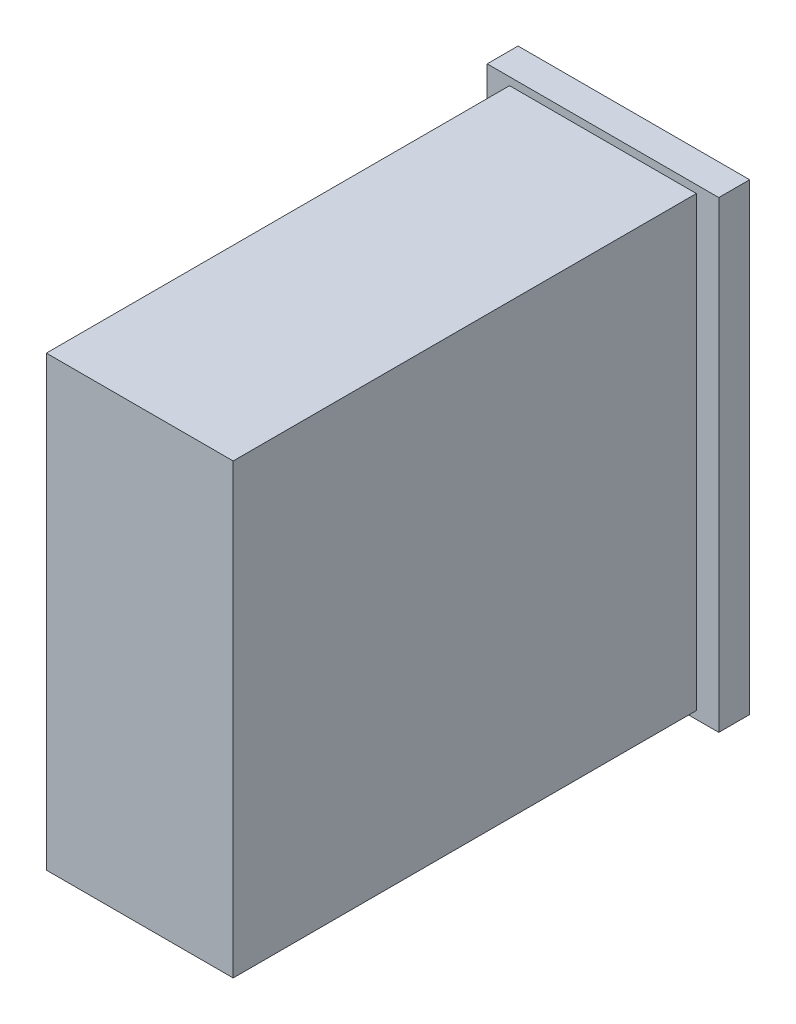
SolidWorks part; units mm, degrees
ref_plane "Plan de face" through (0, 0, 0) normal (0, 0, 1) x (1, 0, 0)
ref_plane "Plan de dessus" through (0, 0, 0) normal (0, 1, 0) x (1, 0, 0)
ref_plane "Plan de droite" through (0, 0, 0) normal (1, 0, 0) x (0, 0, -1)
sketch "Esquisse1" plane through (0, 0, 0) normal (0, 0, 1) x (1, 0, 0)
  line L1 (-7.5, 15) -> (7.5, 15)
  line L2 (-7.5, 15) -> (-7.5, -15)
  line L3 (-7.5, -15) -> (7.5, -15)
  line L4 (7.5, 15) -> (7.5, -15)
  line L5 (-7.5, 15) -> (7.5, -15) construction
  line L6 (-7.5, -15) -> (7.5, 15) construction
  point P0 (0, 0)
  dimension "D1" = 15
  dimension "D2" = 30
extrude "Boss.-Extru.1" add sketch "Esquisse1" along normal blind 2
sketch "Esquisse2" plane through (0, 0, 2) normal (0, 0, 1) x (1, 0, 0)
  line L1 (-6.05, 14.5) -> (6.05, 14.5)
  line L2 (-6.05, 14.5) -> (-6.05, -14.5)
  line L3 (-6.05, -14.5) -> (6.05, -14.5)
  line L4 (6.05, 14.5) -> (6.05, -14.5)
  line L5 (-6.05, 14.5) -> (6.05, -14.5) construction
  line L6 (-6.05, -14.5) -> (6.05, 14.5) construction
  point P0 (0, 0)
  dimension "D1" = 12.1
  dimension "D2" = 29
extrude "Boss.-Extru.2" add sketch "Esquisse2" along normal blind 30
